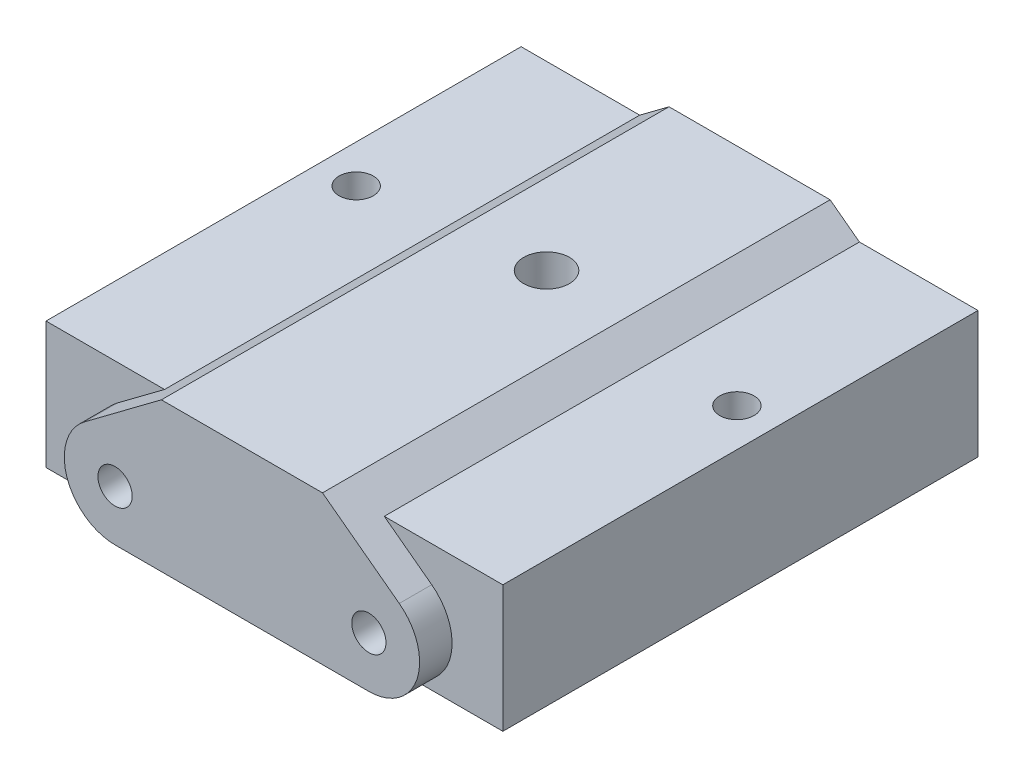
SolidWorks part; units mm, degrees
ref_plane "Front" through (0, 0, 0) normal (0, 0, 1) x (1, 0, 0)
ref_plane "Top" through (0, 0, 0) normal (0, 1, 0) x (1, 0, 0)
ref_plane "Right" through (0, 0, 0) normal (1, 0, 0) x (0, 0, -1)
sketch "草图1" plane through (0, 0, 0) normal (0, 0, 1) x (1, 0, 0)
  line L0 (-10, -4) -> (10, -4)
  line L2 (0, 7.727) -> (-6.3477, 7.727)
  line L3 (-6.3477, 7.727) -> (-12.3959, 3.2031)
  line L4 (0, 7.727) -> (6.3477, 7.727)
  line L5 (6.3477, 7.727) -> (12.3959, 3.2031)
  circle A1 centre (10, 0) radius 1.35
  circle A2 centre (-10, 0) radius 1.35
  arc A3 (-12.3959, 3.2031) -> (-10, -4) centre (-10, 0) ccw
  arc A4 (10, -4) -> (12.3959, 3.2031) centre (10, 0) ccw
  point P0 (-10.2189, -3.994)
  dimension "D1" = 20
extrude "凸台-拉伸1" add sketch "草图1" along normal blind 40
sketch "草图2" plane through (0, -4, 0) normal (0, -1, 0) x (1, 0, 0)
  line L1 (-10, 40) -> (-10, 0) construction
  line L2 (-10, 37.4417) -> (-18, 37.4417)
  line L3 (-18, 37.4417) -> (-18, 0)
  line L4 (-18, 0) -> (0, 0)
  line L5 (0, 0) -> (10, 0)
  line L6 (10, 0) -> (18, 0)
  line L7 (18, 0) -> (18, 37.4417)
  line L8 (18, 37.4417) -> (-10, 37.4417)
extrude "凸台-拉伸2" add sketch "草图2" against normal blind 10
sketch "草图3" plane through (0, -4, 0) normal (0, -1, 0) x (1, 0, 0)
  line L0 (-18, 37.4417) -> (18, 37.4417)
  line L1 (18, 37.4417) -> (18, 0)
  line L2 (18, 0) -> (-18, 0)
  line L3 (-18, 0) -> (-18, 37.4417)
  circle A0 centre (0, 16) radius 11
extrude "凸台-拉伸3" add sketch "草图3" along normal blind 5
sketch "草图4" plane through (0, -4, 0) normal (0, -1, 0) x (1, 0, 0)
  circle A0 centre (0, 16) radius 1.8
extrude "切除-拉伸1" cut sketch "草图4" against normal blind 18
sketch "草图5" plane through (0, -9, 0) normal (0, -1, 0) x (1, 0, 0)
  circle A1 centre (-15, 16) radius 1.35
  circle A2 centre (15, 16) radius 1.35
extrude "切除-拉伸2" cut sketch "草图5" against normal blind 18
sketch "草图6" plane through (0, -4, 0) normal (0, -1, 0) x (1, 0, 0)
  circle A0 centre (0, 16) radius 11
extrude "切除-拉伸3" cut sketch "草图6" against normal blind 5
sketch "草图7" plane through (0, -9, 0) normal (0, -1, 0) x (1, 0, 0)
  line L0 (-18, 37.4417) -> (18, 37.4417)
  line L1 (18, 37.4417) -> (18, 0)
  line L2 (18, 0) -> (18, 37.4417) construction
  line L3 (18, 0) -> (-18, 0)
  line L4 (-18, 0) -> (-18, 37.4417)
extrude "切除-拉伸4" cut sketch "草图7" against normal blind 5
sketch "草图8" plane through (0, 0, 37.4417) normal (0, 0, 1) x (1, 0, 0)
  circle A0 centre (10, 0) radius 1.35
  circle A1 centre (-10, 0) radius 1.35
extrude "切除-拉伸5" cut sketch "草图8" against normal blind 12
sketch "草图10" plane through (0, 0, 0) normal (0, 0, -1) x (-1, 0, 0)
  circle A1 centre (10, 0) radius 1.34
  circle A2 centre (-10, 0) radius 1.35
extrude "切除-拉伸6" cut sketch "草图10" against normal blind 8
